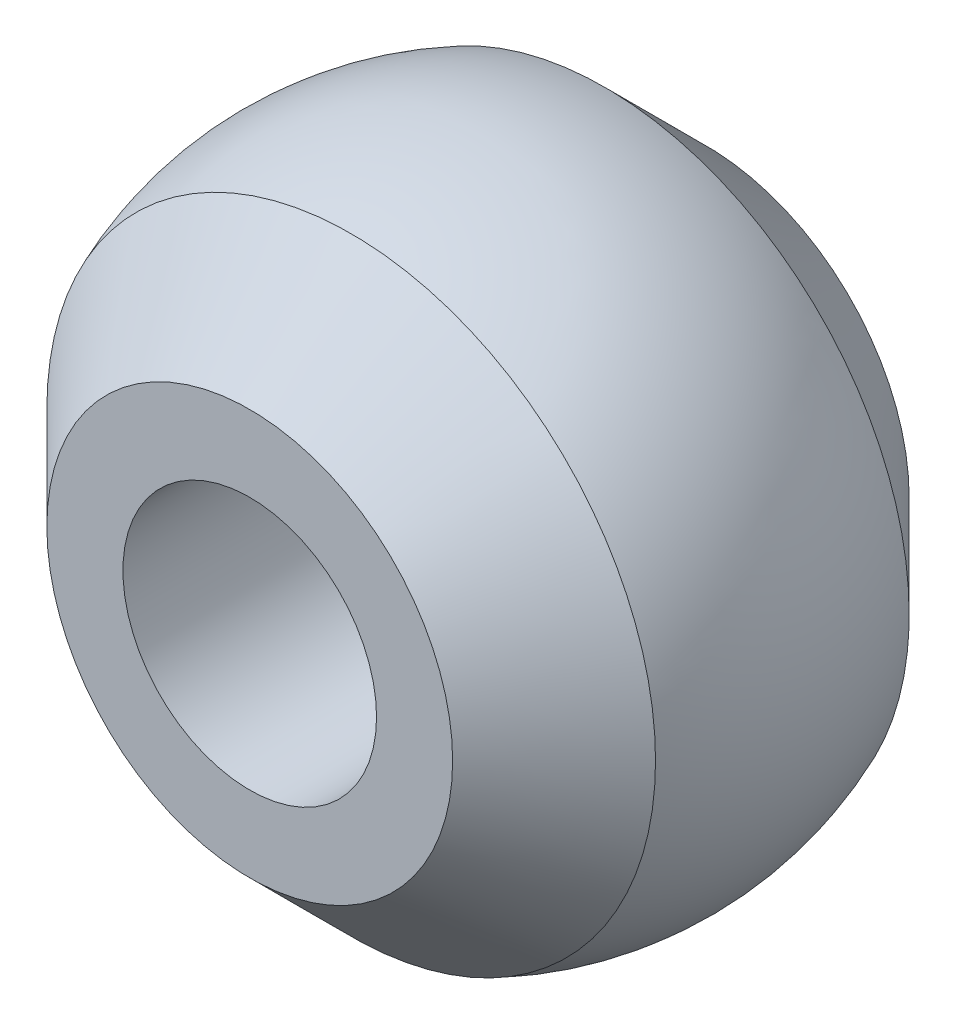
SolidWorks part; units mm, degrees
ref_plane "前视基准面" through (0, 0, 0) normal (0, 0, 1) x (1, 0, 0)
ref_plane "上视基准面" through (0, 0, 0) normal (0, 1, 0) x (1, 0, 0)
ref_plane "右视基准面" through (0, 0, 0) normal (1, 0, 0) x (0, 0, -1)
sketch "草图1" plane through (0, 0, 0) normal (0, 1, 0) x (1, 0, 0)
  circle A0 centre (0, 0) radius 10
  dimension "D1" = 20
extrude "凸台-拉伸1" add sketch "草图1" along normal blind 4.5
sketch "草图4" plane through (0, 0, 0) normal (0, 0, 1) x (1, 0, 0)
  line L0 (10, 4.5) -> (-10, 4.5) construction
  line L1 (-10, 4.5) -> (10, 4.5)
  line L2 (-10, 4.5) -> (-10, 14.5)
  line L4 (10, 4.5) -> (10, 14.5)
  line L5 (0, 193.283) -> (0, 138.3299) construction
  arc A0 (-10, 14.5) -> (10, 14.5) centre (0, 14.5) cw
  circle A1 centre (0, 14.5) radius 8
  dimension "D4" = 16
  dimension "D1" = 10
  dimension "D2" = 10
  dimension "D3" = 10
extrude "凸台-拉伸3" add sketch "草图4" against normal mid plane 10
sketch "草图5" plane through (0, 0, 0) normal (0, 0, 1) x (1, 0, 0)
  circle A0 centre (0, 14.5) radius 8
extrude "凸台-拉伸4" add sketch "草图5" along normal mid plane 5
ref_plane "基准面4" through (0, 0, 4.5) normal (0, 0, 1) x (1, 0, 0)
sketch "草图7" plane through (0, 0, 2.5) normal (0, 0, 1) x (1, 0, 0)
  circle A0 centre (0, 14.5) radius 6
  dimension "D1" = 12
sketch "草图8" plane through (0, 0, 4.5) normal (0, 0, 1) x (1, 0, 0)
  circle A0 centre (0, 14.5) radius 4
  dimension "D1" = 8
loft "放样1" add profiles "草图8", "草图7"
mirror "镜向1" about plane through (0, 0, 0) normal (0, 0, 1) of "放样1"
sketch "草图9" plane through (0, 4.5, 0) normal (0, 1, 0) x (1, 0, 0)
  circle A0 centre (0, 0) radius 10
  circle A1 centre (0, 0) radius 14.6272
extrude "切除-拉伸1" cut sketch "草图9" along normal blind 18
sketch "草图10" plane through (0, 0, 4.5) normal (0, 0, 1) x (1, 0, 0)
  circle A0 centre (0, 14.5) radius 2.5
  dimension "D1" = 5
extrude "切除-拉伸2" cut sketch "草图10" against normal blind 10
sketch "草图2" plane through (0, 0, 0) normal (0, -1, 0) x (1, 0, 0)
  circle A0 centre (0, 0) radius 6
  dimension "D2" = 12
extrude "凸台-拉伸5" add sketch "草图2" along normal blind 80 contours A0
sketch "草图11" plane through (0, 0, 4.5) normal (0, 0, 1) x (1, 0, 0)
  line L1 (-21.2182, 33.1182) -> (23.4246, 33.1182)
  line L2 (-21.2182, 33.1182) -> (-21.2182, -92.4529)
  line L3 (-21.2182, -92.4529) -> (23.4246, -92.4529)
  line L4 (23.4246, 33.1182) -> (23.4246, -92.4529)
  circle A0 centre (0, 14.5) radius 6
  dimension "D1" = 12
extrude "切除-拉伸3" cut sketch "草图11" against normal mid plane 36
sketch "草图13" plane through (0, 0, 0) normal (1, 0, 0) x (0, 0, -1)
  line L0 (-2.5, 20.5) -> (2.5, 20.5)
  line L1 (0, 14.5) -> (7.0594, 14.5) construction
  arc A0 (-2.5, 20.5) -> (2.5, 20.5) centre (0, 14.5) cw
  dimension "D1" = 6.5
revolve "旋转2" add sketch "草图13" angle 360 about L1
